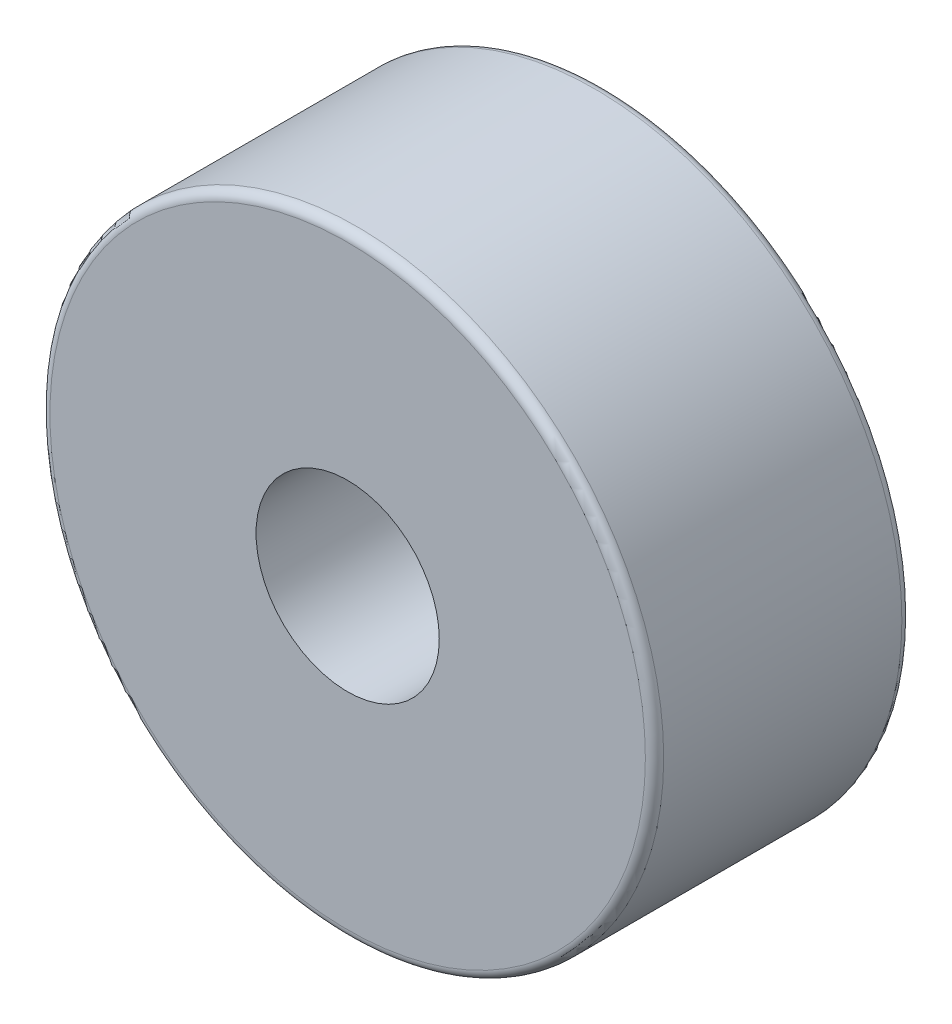
SolidWorks part; units mm, degrees
ref_plane "Plan de face" through (0, 0, 0) normal (0, 0, 1) x (1, 0, 0)
ref_plane "Plan de dessus" through (0, 0, 0) normal (0, 1, 0) x (1, 0, 0)
ref_plane "Plan de droite" through (0, 0, 0) normal (1, 0, 0) x (0, 0, -1)
sketch "Esquisse1" plane through (0, 0, 0) normal (0, 0, 1) x (1, 0, 0)
  circle A0 centre (0, 0) radius 33.5
  circle A1 centre (0, 0) radius 10
  dimension "D1" = 67
  dimension "D2" = 20
extrude "Boss.-Extru.1" add sketch "Esquisse1" along normal blind 28
fillet "Congé1" radius 1 2 edges at (33.5, 0, 28) (33.5, 0, 0)
sketch "Esquisse2" plane through (0, 0, 28) normal (0, 0, 1) x (1, 0, 0)
  line L0 (0, 0) -> (0, 39.2555) construction
  point P5 (12.1858, 33.5)
  point P6 (0, 35.2044)
  point P7 (3.9571, 33.2655)
  point P9 (11.6777, 31.3987)
  point P10 (0, 33.5)
  point P11 (0, 0)
  point P12 (0, 0)
  point P13 (0, 0)
  point P14 (0, 35.138)
  point P17 (15.5113, 37.5)
  point P18 (12.6766, 39.2555)
  point P19 (0, 0)
  point P20 (13.2395, 37.5)
